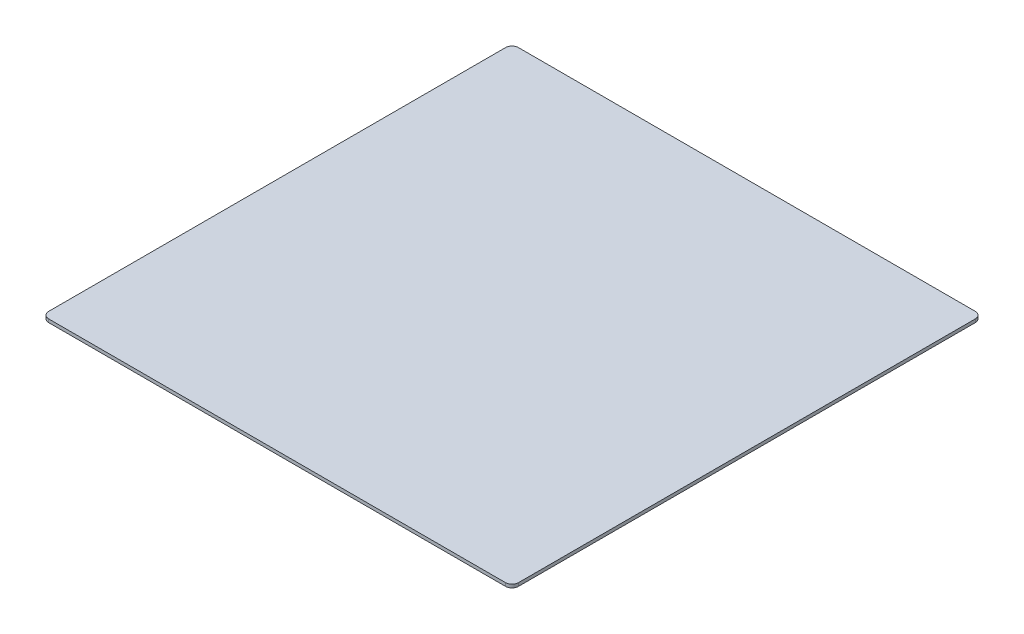
SolidWorks part; units mm, degrees
material "PC High Viscosity"
ref_plane "Front Plane" through (0, 0, 0) normal (0, 0, 1) x (1, 0, 0)
ref_plane "Top Plane" through (0, 0, 0) normal (0, 1, 0) x (1, 0, 0)
ref_plane "Right Plane" through (0, 0, 0) normal (1, 0, 0) x (0, 0, -1)
sketch "Sketch1" plane through (0, 0, 0) normal (0, 1, 0) x (1, 0, 0)
  line L1 (-228.6, -228.6) -> (228.6, -228.6)
  line L2 (-228.6, -228.6) -> (-228.6, 228.6)
  line L3 (-228.6, 228.6) -> (228.6, 228.6)
  line L4 (228.6, -228.6) -> (228.6, 228.6)
  line L5 (-228.6, -228.6) -> (228.6, 228.6) construction
  line L6 (-228.6, 228.6) -> (228.6, -228.6) construction
  point P0 (0, 0)
  dimension "D1" = 457.2
  dimension "D2" = 457.2
extrude "Boss-Extrude1" add sketch "Sketch1" along normal blind 3.175
fillet "Fillet1" radius 6.35 4 edges at (-228.6, 1.5875, -228.6) (228.6, 1.5875, -228.6) (228.6, 1.5875, 228.6) (-228.6, 1.5875, 228.6)
